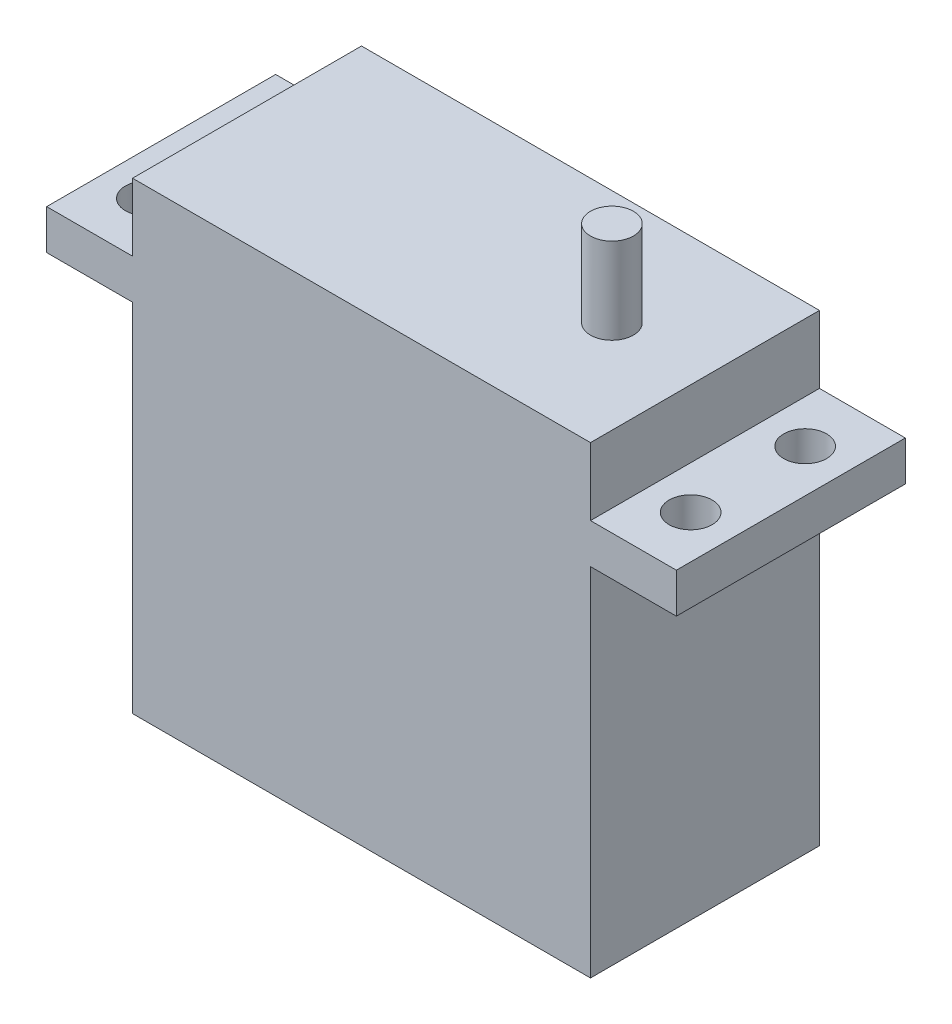
SolidWorks part; units mm, degrees
ref_plane "Front Plane" through (0, 0, 0) normal (0, 0, 1) x (1, 0, 0)
ref_plane "Top Plane" through (0, 0, 0) normal (0, 1, 0) x (1, 0, 0)
ref_plane "Right Plane" through (0, 0, 0) normal (1, 0, 0) x (0, 0, -1)
sketch "Sketch1" plane through (0, 0, 0) normal (0, 1, 0) x (1, 0, 0)
  line L1 (0, 0) -> (40, 0)
  line L2 (0, 0) -> (0, 20)
  line L3 (0, 20) -> (40, 20)
  line L4 (40, 0) -> (40, 20)
  dimension "D1" = 40
  dimension "D2" = 20
extrude "Boss-Extrude1" add sketch "Sketch1" along normal blind 40.5
sketch "Sketch2" plane through (40, 0, 0) normal (1, 0, 0) x (0, 0, -1)
  line L0 (0, 40.5) -> (0, 0) construction
  line L1 (0, 31.12) -> (20, 31.12)
  line L2 (0, 31.12) -> (0, 34.6)
  line L3 (0, 34.6) -> (20, 34.6)
  line L4 (20, 31.12) -> (20, 34.6)
  line L5 (20, 40.5) -> (20, 0) construction
  line L6 (0, 40.5) -> (20, 40.5) construction
  dimension "D1" = 5.9
  dimension "D2" = 3.48
extrude "Boss-Extrude2" add sketch "Sketch2" along normal blind 7.5 and the other way blind 47.5
sketch "Sketch3" plane through (0, 34.6, 0) normal (0, 1, 0) x (1, 0, 0)
  line L0 (-7.5, 20) -> (0, 20) construction
  line L1 (40, 20) -> (47.5, 20) construction
  circle A0 centre (43.75, 15) radius 1.875
  circle A1 centre (43.75, 5) radius 1.875
  circle A2 centre (-3.75, 15) radius 1.875
  circle A3 centre (-3.75, 5) radius 1.875
  point P13 (-3.75, 20)
  point P22 (43.75, 20)
  dimension "D1" = 3.75
  dimension "D2" = 5
  dimension "D3" = 15
extrude "Cut-Extrude1" cut sketch "Sketch3" against normal through all
sketch "Sketch4" plane through (0, 40.5, 0) normal (0, 1, 0) x (1, 0, 0)
  line L3 (47.5, 20) -> (47.5, 0) construction
  circle A0 centre (31.8724, 10) radius 1.875
  point P9 (47.5, 10)
  dimension "D1" = 3.75
  dimension "D2" = 15.6276
extrude "Boss-Extrude3" add sketch "Sketch4" along normal blind 7.5
